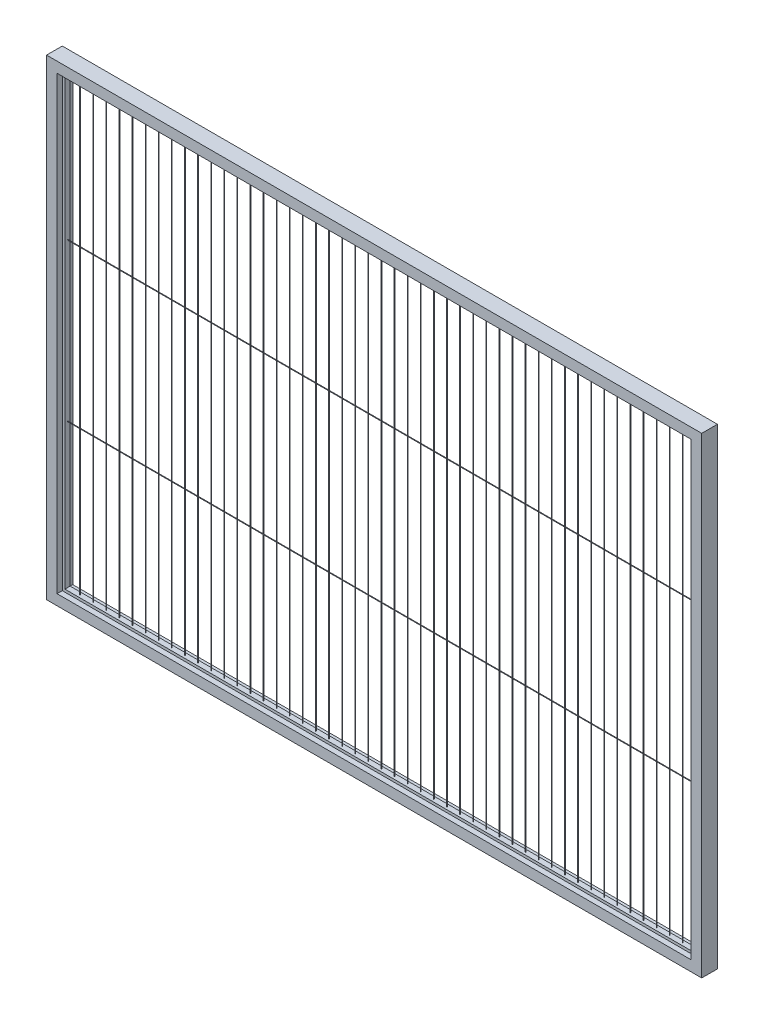
SolidWorks part; units mm, degrees
ref_plane "前视基准面" through (0, 0, 0) normal (0, 0, 1) x (1, 0, 0)
ref_plane "上视基准面" through (0, 0, 0) normal (0, 1, 0) x (1, 0, 0)
ref_plane "右视基准面" through (0, 0, 0) normal (1, 0, 0) x (0, 0, -1)
sketch "草图1" plane through (0, 0, 0) normal (1, 0, 0) x (0, 0, -1)
  line L0 (30, 0) -> (-30, 0)
  line L1 (-30, 0) -> (-30, 40)
  line L2 (-30, 40) -> (-10, 40)
  line L3 (-10, 40) -> (-10, 50)
  line L4 (-10, 50) -> (10, 50)
  line L5 (0, 0) -> (0, 164.1985) construction
  line L6 (10, 40) -> (10, 50)
  line L7 (30, 40) -> (10, 40)
  line L8 (30, 0) -> (30, 40)
  line L9 (-155.4817, 900) -> (236.5603, 900) construction
  line L10 (30, 1800) -> (30, 1760)
  line L11 (30, 1760) -> (10, 1760)
  line L12 (10, 1760) -> (10, 1750)
  line L13 (-10, 1750) -> (10, 1750)
  line L14 (-10, 1760) -> (-10, 1750)
  line L15 (-30, 1760) -> (-10, 1760)
  line L16 (-30, 1800) -> (-30, 1760)
  line L17 (30, 1800) -> (-30, 1800)
  point P9 (0, 50)
  point P22 (0, 1750)
  dimension "D1" = 60
  dimension "D2" = 40
  dimension "D3" = 50
  dimension "D4" = 900
  dimension "D5" = 20
extrude "凸台-拉伸1" add sketch "草图1" along normal mid plane 2500
sketch "草图3" plane through (0, 1760, 0) normal (0, -1, 0) x (1, 0, 0)
  line L0 (-1250, -30) -> (-1250, 30)
  line L1 (-1250, 30) -> (-1210, 30)
  line L2 (1250, 30) -> (-1250, 30) construction
  line L3 (-1210, 30) -> (-1210, 10)
  line L4 (-1210, 10) -> (-1200, 10)
  line L5 (-1200, 10) -> (-1200, -10)
  line L6 (-1200, -10) -> (-1210, -10)
  line L7 (-1210, -10) -> (-1210, -30)
  line L8 (1250, -30) -> (-1250, -30) construction
  line L9 (-1210, -30) -> (-1250, -30)
  line L10 (-1250, 0) -> (-1150.2083, 0) construction
  line L11 (0, 0) -> (0, 199.5388) construction
  line L12 (1250, 0) -> (1150.2083, 0) construction
  line L13 (1210, -30) -> (1250, -30)
  line L14 (1210, -10) -> (1210, -30)
  line L15 (1200, -10) -> (1210, -10)
  line L16 (1200, 10) -> (1200, -10)
  line L17 (1210, 10) -> (1200, 10)
  line L18 (1210, 30) -> (1210, 10)
  line L19 (1250, 30) -> (1210, 30)
  line L20 (1250, -30) -> (1250, 30)
  dimension "D1" = 40
  dimension "D2" = 50
  dimension "D3" = 20
extrude "凸台-拉伸2" add sketch "草图3" along normal up to surface (1720 mm away) separate body up to face at (0, 40, 20)
sketch "草图4" plane through (0, 1760, 0) normal (0, -1, 0) x (1, 0, 0)
  line L0 (1250, -30) -> (-1250, -30) construction
  line L1 (-1250, 30) -> (-1200, 30)
  line L2 (-1250, 30) -> (-1250, -30)
  line L3 (-1250, -30) -> (-1200, -30)
  line L4 (-1200, 30) -> (-1200, -30)
  line L5 (0, 0) -> (0, 218.547) construction
  line L6 (1200, 30) -> (1200, -30)
  line L7 (1250, -30) -> (1200, -30)
  line L8 (1250, 30) -> (1250, -30)
  line L9 (1250, 30) -> (1200, 30)
  dimension "D1" = 50
extrude "切除-拉伸1" cut sketch "草图4" along normal blind 10
sketch "草图5" plane through (0, 40, 0) normal (0, 1, 0) x (1, 0, 0)
  line L0 (1250, -30) -> (-1250, -30) construction
  line L1 (-1250, 30) -> (-1200, 30)
  line L2 (-1250, 30) -> (-1250, -30)
  line L3 (-1250, -30) -> (-1200, -30)
  line L4 (-1200, 30) -> (-1200, -30)
  line L5 (0, 0) -> (0, 304.5992) construction
  line L6 (1200, 30) -> (1200, -30)
  line L7 (1250, -30) -> (1200, -30)
  line L8 (1250, 30) -> (1250, -30)
  line L9 (1250, 30) -> (1200, 30)
  dimension "50" = 50
extrude "切除-拉伸2" cut sketch "草图5" along normal blind 10
sketch "草图6" plane through (1200, 0, 0) normal (-1, 0, 0) x (0, 0, 1)
  line L0 (0, 1800) -> (0, 0) construction
  line L1 (-30, 1800) -> (30, 1800) construction
  circle A0 centre (0, 1200) radius 1
  dimension "D1" = 2
  dimension "D2" = 600
extrude "凸台-拉伸3" add sketch "草图6" along normal up to next (2400 mm away) contours A0
pattern_linear "阵列(线性)1" count 2 spacing 600 along (0, -1, 0) of "凸台-拉伸3"
sketch "草图8" plane through (0, 1750, 0) normal (0, -1, 0) x (1, 0, 0)
  line L0 (-1250, 0) -> (1250, 0) construction
  line L1 (-1250, 30) -> (-1250, -30) construction
  line L2 (1250, 30) -> (1250, -30) construction
  circle A0 centre (-1152, 0) radius 1
  dimension "D1" = 2
  dimension "D2" = 98
extrude "凸台-拉伸4" add sketch "草图8" along normal up to surface (1700 mm away) up to face at (0, 50, 0)
pattern_linear "阵列(线性)2" count 48 spacing 50 along (1, 0, 0) of "凸台-拉伸4"
